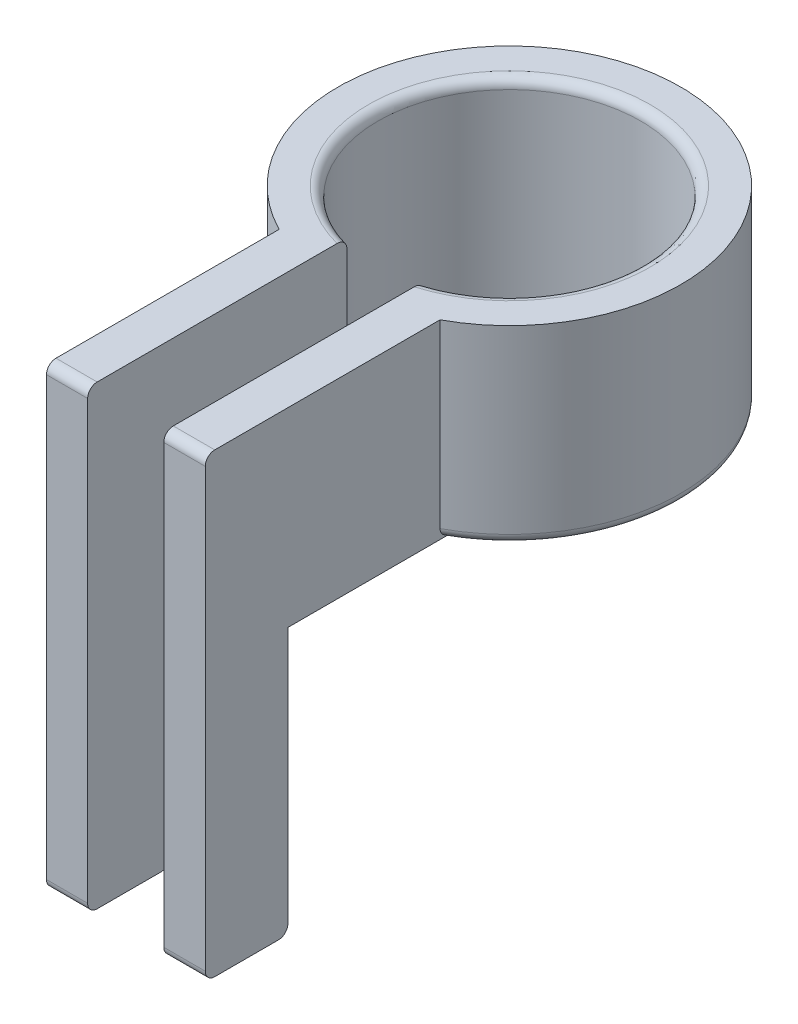
SolidWorks part; units mm, degrees
ref_plane "Front Plane" through (0, 0, 0) normal (0, 0, 1) x (1, 0, 0)
ref_plane "Top Plane" through (0, 0, 0) normal (0, 1, 0) x (1, 0, 0)
ref_plane "Right Plane" through (0, 0, 0) normal (1, 0, 0) x (0, 0, -1)
sketch "Sketch1" plane through (0, 0, 0) normal (0, 1, 0) x (1, 0, 0)
  circle A0 centre (0, 0) radius 6.9
  circle A1 centre (0, 0) radius 9
extrude "Boss-Extrude1" add sketch "Sketch1" along normal blind 10
sketch "Sketch2" plane through (0, 10, 0) normal (0, 1, 0) x (1, 0, 0)
  line L1 (-1.9029, -12.9634) -> (2.0971, -12.9634)
  line L2 (-1.9029, -12.9634) -> (-1.9029, -5.1981)
  line L3 (-1.9029, -5.1981) -> (2.0971, -5.1981)
  line L4 (2.0971, -12.9634) -> (2.0971, -5.1981)
extrude "Cut-Extrude1" cut sketch "Sketch2" against normal blind 14
sketch "Sketch3" plane through (0, 10, 0) normal (0, 1, 0) x (1, 0, 0)
  line L1 (2.0971, -20.7545) -> (4.2757, -20.7545)
  line L2 (2.0971, -20.7545) -> (2.0971, -6.5736)
  line L3 (2.0971, -6.5736) -> (4.2757, -6.5736)
  line L4 (4.2757, -20.7545) -> (4.2757, -6.5736)
  line L5 (-1.9029, -20.7545) -> (-4.0671, -20.7545)
  line L6 (-1.9029, -20.7545) -> (-1.9029, -6.6324)
  line L7 (-1.9029, -6.6324) -> (-4.0671, -6.6324)
  line L8 (-4.0671, -20.7545) -> (-4.0671, -6.6324)
extrude "Boss-Extrude2" add sketch "Sketch3" against normal blind 10
sketch "Sketch4" plane through (0, -13.9703, 0) normal (0, 1, 0) x (1, 0, 0)
  line L0 (2.0971, -20.7545) -> (2.0971, -6.5736) construction
  line L1 (4.2757, -20.7545) -> (2.0971, -20.7545)
  line L2 (4.2757, -20.7545) -> (4.2757, -12.9634)
  line L3 (4.2757, -12.9634) -> (2.0971, -12.9634)
  line L4 (2.0971, -20.7545) -> (2.0971, -12.9634)
  line L5 (-1.9029, -12.9634) -> (2.0971, -12.9634) construction
  line L6 (-1.9029, -6.6324) -> (-1.9029, -20.7545) construction
  line L7 (-4.0671, -20.7545) -> (-1.9029, -20.7545)
  line L8 (-4.0671, -20.7545) -> (-4.0671, -12.9634)
  line L9 (-4.0671, -12.9634) -> (-1.9029, -12.9634)
  line L10 (-1.9029, -20.7545) -> (-1.9029, -12.9634)
  line L11 (-1.4029, -13.4634) -> (-1.9029, -12.9634) construction
extrude "Boss-Extrude3" add sketch "Sketch4" along normal blind 18
sketch "Sketch5" plane through (0, 0, 0) normal (0, -1, 0) x (-1, 0, 0)
  line L1 (-4.2757, -12.9634) -> (18.7477, -12.9634)
  line L2 (-4.2757, -12.9634) -> (-4.2757, -15.91)
  line L3 (-4.2757, -15.91) -> (18.7477, -15.91)
  line L4 (18.7477, -12.9634) -> (18.7477, -15.91)
extrude "Cut-Extrude2" cut sketch "Sketch5" along normal blind 18
sketch "Sketch6" plane through (0, 0, 20.7545) normal (0, 0, 1) x (1, 0, 0)
  circle A0 centre (-4.0671, 10) radius 37.135
extrude "Cut-Extrude3" cut sketch "Sketch6" against normal blind 0.5
fillet "Fillet1" radius 0.5 6 edges at (3.1864, -13.9703, 15.91) (-2.985, -13.9703, 15.91) (-2.985, -13.9703, 20.2545) (3.1864, -13.9703, 20.2545) (3.1864, 10, 20.2545) (-2.985, 10, 20.2545)
fillet "Fillet2" radius 0.5 1 edges at (-0.1177, 0, -8.9992)
fillet "Fillet3" radius 0.5 1 edges at (-0.1014, 10, -6.8993)
